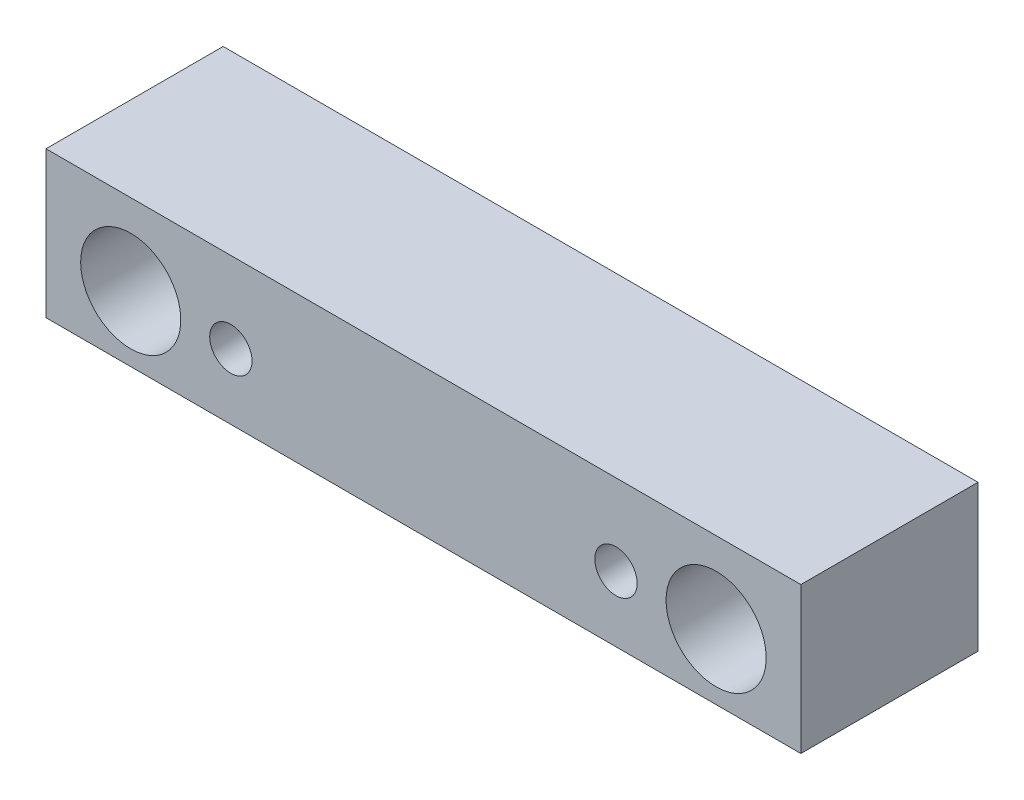
SolidWorks part; units mm, degrees
ref_plane "Спереди" through (0, 0, 0) normal (0, 0, 1) x (1, 0, 0)
ref_plane "Сверху" through (0, 0, 0) normal (0, 1, 0) x (1, 0, 0)
ref_plane "Справа" through (0, 0, 0) normal (1, 0, 0) x (0, 0, -1)
ref_plane "Плоскость4" through (0, 0, 46) normal (0, 0, 1) x (1, 0, 0)
sketch "Эскиз1" plane through (0, 0, 46) normal (0, 0, 1) x (1, 0, 0)
  line L0 (-98, 98) -> (-98, 60)
  line L1 (-98, 60) -> (98, 60)
  line L2 (98, 60) -> (98, 98)
  line L3 (98, 98) -> (-98, 98)
  circle A0 centre (-50, 76.9999) radius 5.5
  circle A1 centre (50, 76.9999) radius 5.5
  circle A2 centre (-76, 77) radius 13
  circle A3 centre (76, 77) radius 13
extrude "Бобышка-Вытянуть1" add sketch "Эскиз1" against normal blind 46
